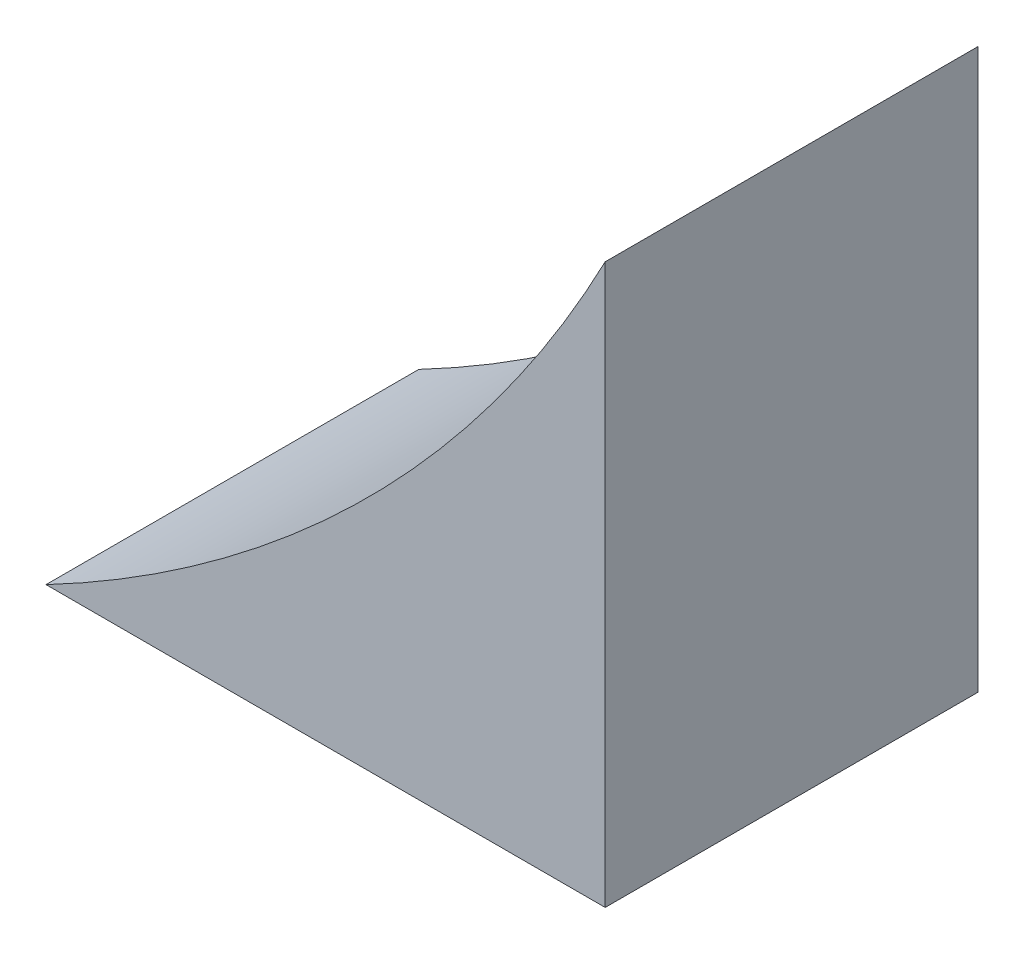
SolidWorks part; units mm, degrees
ref_plane "前视基准面" through (0, 0, 0) normal (0, 0, 1) x (1, 0, 0)
ref_plane "上视基准面" through (0, 0, 0) normal (0, 1, 0) x (1, 0, 0)
ref_plane "右视基准面" through (0, 0, 0) normal (1, 0, 0) x (0, 0, -1)
other "Configuration Table"
sketch "草图1" plane through (0, 0, 0) normal (0, 0, 1) x (1, 0, 0)
  line L5 (0, 0) -> (150, 0)
  line L6 (0, 0) -> (0, 150)
  line L7 (0, 150) -> (150, 150)
  line L8 (150, 0) -> (150, 150)
  dimension "D1" = 150
  dimension "D2" = 150
extrude "凸台-拉伸1" add sketch "草图1" along normal blind 100
sketch "草图2" plane through (0, 0, 100) normal (0, 0, 1) x (1, 0, 0)
  line L0 (150, 0) -> (0, 150)
  line L1 (0, 150) -> (-447.8279, 597.8279)
  circle A1 centre (-164.5569, 314.5569) radius 355
extrude "切除-拉伸1" cut sketch "草图2" against normal blind 1000 contours A1
